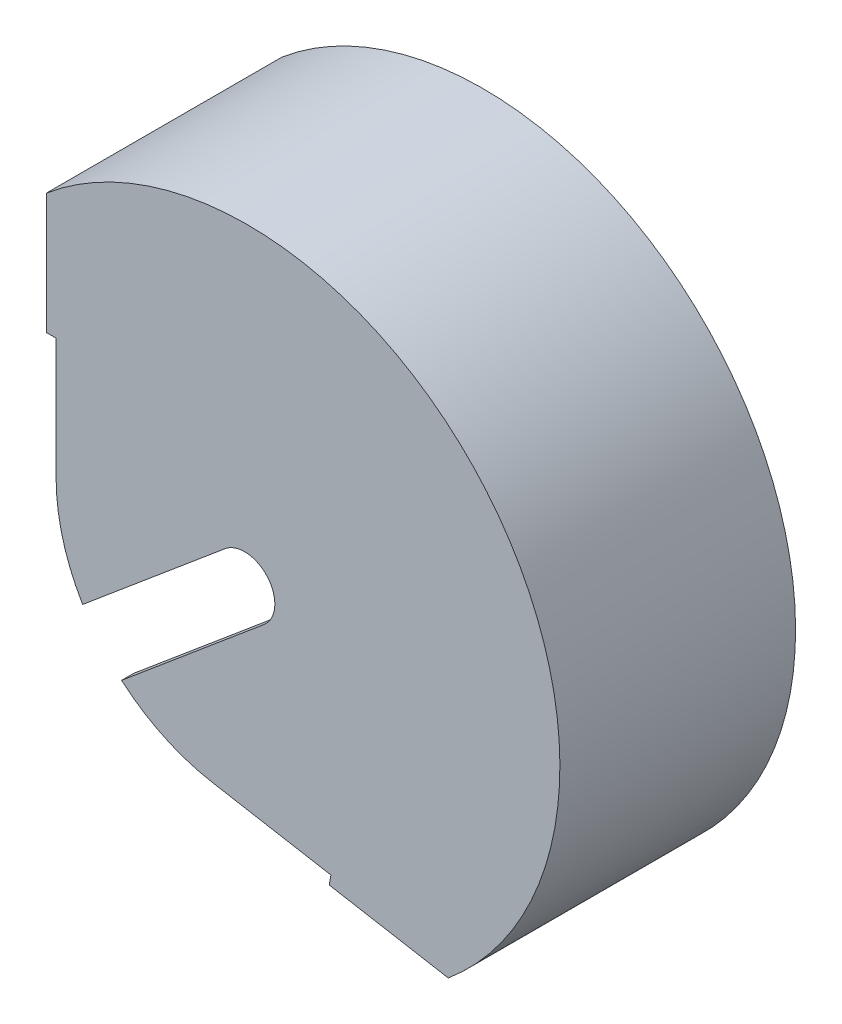
SolidWorks part; units mm, degrees
ref_plane "Front Plane" through (0, 0, 0) normal (0, 0, 1) x (1, 0, 0)
ref_plane "Top Plane" through (0, 0, 0) normal (0, 1, 0) x (1, 0, 0)
ref_plane "Right Plane" through (0, 0, 0) normal (1, 0, 0) x (0, 0, -1)
sketch "Sketch1" plane through (0, 0, 0) normal (0, 0, 1) x (1, 0, 0)
  line L0 (0, 0) -> (-39.624, 0)
  line L1 (0, 0) -> (-6.8806, -39.022)
  line L2 (-39.624, 0) -> (-39.624, 25.4)
  line L3 (-6.8806, -39.022) -> (18.1335, -43.4327)
  line L4 (-39.624, 25.4) -> (-41.656, 25.4)
  line L5 (18.1335, -43.4327) -> (17.7806, -45.4338)
  line L6 (-41.656, 25.4) -> (-41.656, 50.8)
  line L7 (17.7806, -45.4338) -> (42.7947, -49.8445)
  arc A0 (-39.624, 0) -> (-6.8806, -39.022) centre (0, 0) ccw
  arc A1 (42.7947, -49.8445) -> (-41.656, 50.8) centre (0.5694, 0.4778) ccw
  dimension "D1" = 79.248
  dimension "D2" = 80
  dimension "D3" = 25.4
  dimension "D4" = 25.4
  dimension "D5" = 2.032
  dimension "D6" = 2.032
  dimension "D7" = 25.4
extrude "Side" add sketch "Sketch1" along normal blind 2.54 contours L7 A1 L6 L4 L2 L0 L1 L3 L5 | L0 A0 L1
sketch "Sketch2" plane through (0, 0, 2.54) normal (0, 0, 1) x (1, 0, 0)
  line L0 (-40.0233, 48.8542) -> (-41.656, 48.8542)
  line L2 (41.1621, -47.8987) -> (40.8786, -49.5066)
  line L4 (-41.656, 25.4) -> (-41.656, 50.8) construction
  line L5 (17.7806, -45.4338) -> (42.7947, -49.8445) construction
  line L6 (-41.656, 48.8542) -> (-41.656, 50.8)
  line L7 (40.8786, -49.5066) -> (42.7947, -49.8445)
  arc A2 (41.1621, -47.8987) -> (-40.0233, 48.8542) centre (0.5694, 0.4778) ccw
  arc A3 (41.1621, -47.8987) -> (-40.0233, 48.8542) centre (0.5694, 0.4778) ccw
  arc A5 (42.7947, -49.8445) -> (-41.656, 50.8) centre (0.5694, 0.4778) ccw
  arc A6 (42.7947, -49.8445) -> (-41.656, 50.8) centre (0.5694, 0.4778) ccw
  line M6 (18.1335, -43.4327) -> (17.7806, -45.4338)
  line M7 (17.7806, -45.4338) -> (42.7947, -49.8445)
  arc M8 (42.7947, -49.8445) -> (-41.656, 50.8) centre (0.5694, 0.4778) ccw
  line M9 (-41.656, 50.8) -> (-41.656, 25.4)
  line M10 (-41.656, 25.4) -> (-39.624, 25.4)
  dimension "D1" = 2.54
  dimension "D2" = 0
extrude "Cover" add sketch "Sketch2" along normal blind 44.45 contours A3 L2 L0 M6 M7 M8 M9 M10
ref_plane "midplane" through (0, 0, 24.765) normal (0, 0, 1) x (1, 0, 0)
mirror "Mirror1" about plane through (0, 0, 24.765) normal (0, 0, 1) of "Side"
sketch "Sketch3" plane through (0, 0, 49.53) normal (0, 0, 1) x (1, 0, 0)
  line L0 (0, 0) -> (-30.3537, -25.4698) construction
  line L1 (-4.0817, 4.8644) -> (-37.1595, -22.8912)
  line L2 (-37.1595, -22.8912) -> (-28.9961, -32.62)
  line L3 (-28.9961, -32.62) -> (4.0817, -4.8644)
  arc A0 (4.0817, -4.8644) -> (-4.0817, 4.8644) centre (0, 0) ccw
  arc A1 (-39.624, 0) -> (-6.8806, -39.022) centre (0, 0) ccw construction
  dimension "D2" = 12.7
  dimension "D1" = 43.18
extrude "Flywheel slit" cut sketch "Sketch3" against normal up to next
sketch "Sketch4" plane through (0, 0, 0) normal (0, 0, -1) x (-1, 0, 0)
  line L0 (0, 0) -> (39.624, 0) construction
  line L1 (0, 0) -> (33.2775, 10.174) construction
  line L2 (-2.1162, -33.5317) -> (33.2775, 10.174) construction
  line L3 (33.2775, 10.174) -> (3.2382, -36.9452) construction
  line L4 (3.2382, -36.9452) -> (-2.1162, -33.5317) construction
  circle A2 centre (-2.1162, -33.5317) radius 3.2639
  circle A3 centre (33.2775, 10.174) radius 3.2639
  dimension "D1" = 6.35
  dimension "D2" = 55.88
  dimension "D4" = 6.5278
  dimension "D5" = 17
extrude "Mount holes" cut sketch "Sketch4" against normal up to next
sketch "Sketch5" plane through (0, 0, 0) normal (0, 0, -1) x (-1, 0, 0)
  circle A0 centre (0, 0) radius 5.08
  arc A1 (4.0817, 4.8644) -> (-4.0817, -4.8644) centre (0, 0) ccw construction
  dimension "D1" = 10.16
extrude "Axle Holder Hole" cut sketch "Sketch5" against normal up to next
